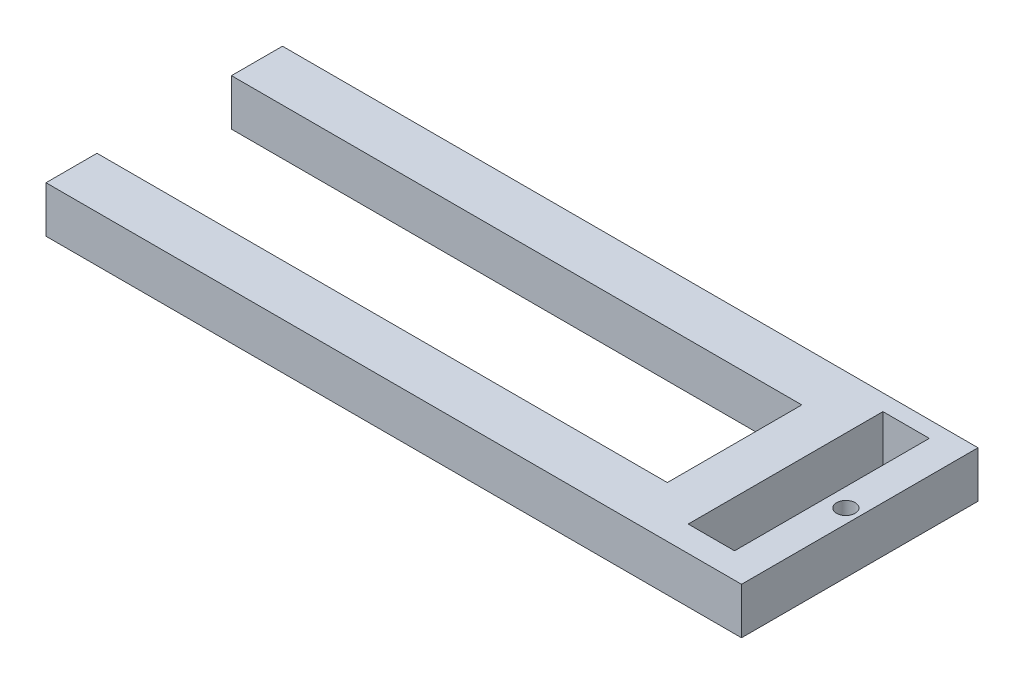
SolidWorks part; units mm, degrees
material "Balsa"
ref_plane "Plan de face" through (0, 0, 0) normal (0, 0, 1) x (1, 0, 0)
ref_plane "Plan de dessus" through (0, 0, 0) normal (0, 1, 0) x (1, 0, 0)
ref_plane "Plan de droite" through (0, 0, 0) normal (1, 0, 0) x (0, 0, -1)
sketch "Sketch1" plane through (0, 0, 0) normal (0, 1, 0) x (1, 0, 0)
  line L1 (-75, -25.5) -> (75, -25.5)
  line L2 (-75, -25.5) -> (-75, 25.5)
  line L3 (-75, 25.5) -> (75, 25.5)
  line L4 (75, -25.5) -> (75, 25.5)
  line L5 (-75, -25.5) -> (75, 25.5) construction
  line L6 (-75, 25.5) -> (75, -25.5) construction
  point P0 (0, 0)
  dimension "D1" = 51
  dimension "D2" = 150
extrude "Boss-Extrude1" add sketch "Sketch1" along normal blind 10
sketch "Sketch2" plane through (0, 10, 0) normal (0, 1, 0) x (1, 0, 0)
  line L0 (-75, -25.5) -> (75, -25.5) construction
  line L1 (58, -20) -> (68, -20)
  line L2 (58, -20) -> (58, 22)
  line L3 (58, 22) -> (68, 22)
  line L4 (68, -20) -> (68, 22)
  line L5 (58, -20) -> (68, 22) construction
  line L6 (58, 22) -> (68, -20) construction
  line L8 (75, -25.5) -> (75, 25.5) construction
  point P0 (63, 1)
  dimension "D1" = 10
  dimension "D2" = 42
  dimension "D3" = 5.5
  dimension "D4" = 12
extrude "Cut-Extrude1" cut sketch "Sketch2" against normal through all
sketch "Sketch3" plane through (0, 10, 0) normal (0, 1, 0) x (1, 0, 0)
  line L1 (-75, 25.5) -> (-75, -25.5) construction
  line L2 (-75, -14.5) -> (48, -14.5)
  line L3 (-75, -14.5) -> (-75, 14.5)
  line L4 (-75, 14.5) -> (48, 14.5)
  line L5 (48, -14.5) -> (48, 14.5)
  line L6 (58, 22) -> (58, -20) construction
  line L8 (-75, -25.5) -> (75, -25.5) construction
  line L10 (75, 25.5) -> (-75, 25.5) construction
  dimension "D1" = 10
  dimension "D2" = 11
  dimension "D3" = 11
extrude "Cut-Extrude2" cut sketch "Sketch3" against normal through all
sketch "Sketch4" plane through (0, 10, 0) normal (0, 1, 0) x (1, 0, 0)
  line L0 (75, -25.5) -> (75, 25.5) construction
  circle A0 centre (72, 0) radius 2
  dimension "D2" = 4
  dimension "D1" = 3
extrude "Cut-Extrude3" cut sketch "Sketch4" against normal through all
